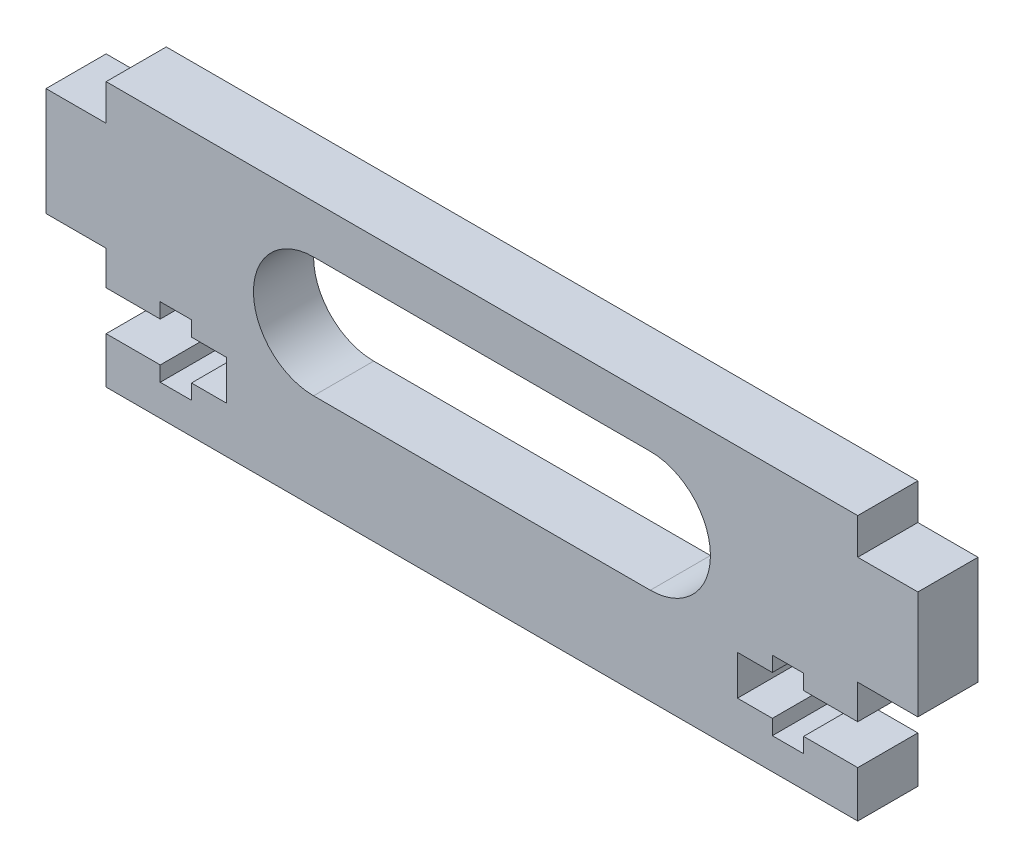
SolidWorks part; units mm, degrees
ref_plane "Спереди" through (0, 0, 0) normal (0, 0, 1) x (1, 0, 0)
ref_plane "Сверху" through (0, 0, 0) normal (0, 1, 0) x (1, 0, 0)
ref_plane "Справа" through (0, 0, 0) normal (1, 0, 0) x (0, 0, -1)
other "Configuration Table"
sketch "Eskiz_kontur" plane through (0, 0, 0) normal (0, 0, 1) x (1, 0, 0)
  line L0 (32.5, 12) -> (27.5, 12)
  line L1 (27.5, 12) -> (27.5, 9.15)
  line L2 (32.5, 21) -> (32.5, 12)
  line L3 (27.5, 9.15) -> (23, 9.15)
  line L4 (27.5, 21) -> (32.5, 21)
  line L5 (23, 9.15) -> (23, 10.4)
  line L6 (27.5, 24) -> (27.5, 21)
  line L7 (23, 10.4) -> (20.4, 10.4)
  line L8 (-35, 24) -> (27.5, 24)
  line L9 (20.4, 10.4) -> (20.4, 9.15)
  line L10 (-35, 21) -> (-35, 24)
  line L11 (20.4, 9.15) -> (17.5, 9.15)
  line L12 (-40, 21) -> (-35, 21)
  line L13 (17.5, 9.15) -> (17.5, 5.85)
  line L14 (-40, 12) -> (-40, 21)
  line L15 (17.5, 5.85) -> (20.4, 5.85)
  line L16 (-35, 12) -> (-40, 12)
  line L17 (20.4, 5.85) -> (20.4, 4.6)
  line L18 (-35, 9.15) -> (-35, 12)
  line L19 (20.4, 4.6) -> (23, 4.6)
  line L20 (-30.5, 9.15) -> (-35, 9.15)
  line L21 (23, 4.6) -> (23, 5.85)
  line L22 (-30.5, 10.4) -> (-30.5, 9.15)
  line L23 (23, 5.85) -> (27.5, 5.85)
  line L24 (-27.9, 10.4) -> (-30.5, 10.4)
  line L25 (27.5, 5.85) -> (27.5, 2)
  line L26 (-27.9, 9.15) -> (-27.9, 10.4)
  line L27 (27.5, 2) -> (-35, 2)
  line L28 (-25, 9.15) -> (-27.9, 9.15)
  line L29 (-35, 2) -> (-35, 5.85)
  line L30 (-25, 5.85) -> (-25, 9.15)
  line L31 (-35, 5.85) -> (-30.5, 5.85)
  line L32 (-27.9, 5.85) -> (-25, 5.85)
  line L33 (-30.5, 5.85) -> (-30.5, 4.6)
  line L34 (-27.9, 4.6) -> (-27.9, 5.85)
  line L35 (-30.5, 4.6) -> (-27.9, 4.6)
  line L36 (10.25, 20) -> (-17.75, 20)
  line L37 (-17.75, 10) -> (10.25, 10)
  arc A0 (-17.75, 20) -> (-17.75, 10) centre (-17.75, 15) ccw
  arc A1 (10.25, 10) -> (10.25, 20) centre (10.25, 15) ccw
extrude "Plastina" add sketch "Eskiz_kontur" along normal blind 5
equation "\"T3\" = 3"
equation "\"T5\" = 5"
equation "\"D_M3\" = 3.3"
equation "\"D_M2\" = 2.2"
equation "\"D_M3_TAP\" = 2.5"
equation "\"D_M4\" = 4.5"
equation "\"L1\" = 100"
equation "\"L2\" = 100"
equation "\"D1@Plastina\" = \"T5\""
